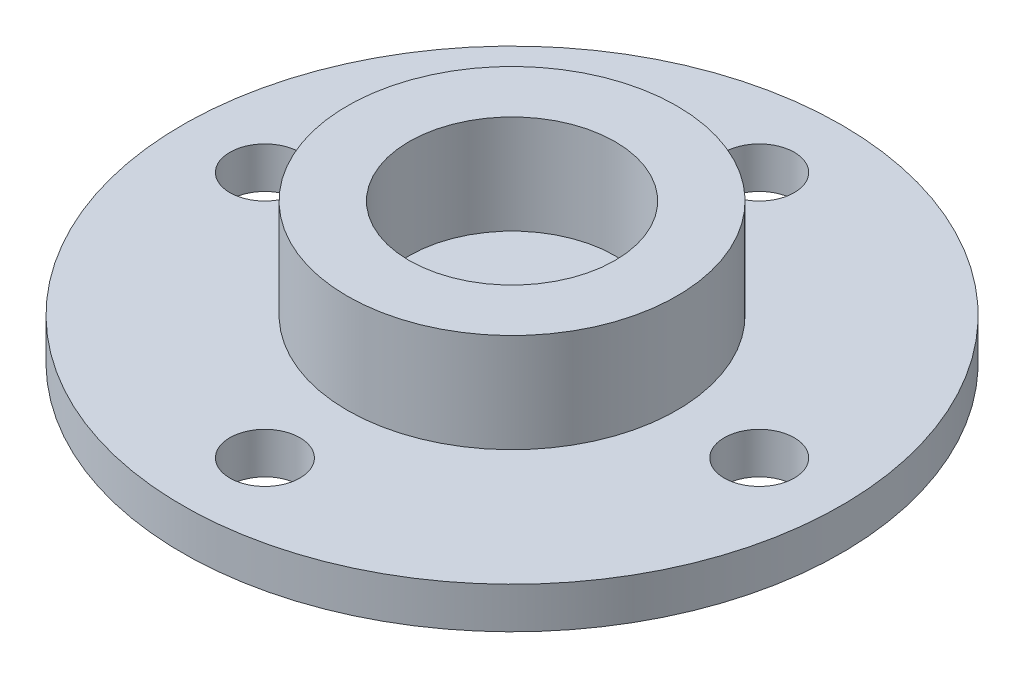
SolidWorks part; units mm, degrees
ref_plane "Front Plane" through (0, 0, 0) normal (0, 0, 1) x (1, 0, 0)
ref_plane "Top Plane" through (0, 0, 0) normal (0, 1, 0) x (1, 0, 0)
ref_plane "Right Plane" through (0, 0, 0) normal (1, 0, 0) x (0, 0, -1)
sketch "Sketch1" plane through (0, 0, 0) normal (0, 0, 1) x (1, 0, 0)
  line L0 (4.5, 5) -> (12.5, 5)
  line L1 (12.5, 5) -> (12.5, 17)
  line L2 (12.5, 17) -> (20, 17)
  line L3 (20, 17) -> (20, 5)
  line L4 (20, 5) -> (40, 5)
  line L5 (40, 5) -> (40, 0)
  line L6 (40, 0) -> (4.5, 0)
  line L7 (4.5, 0) -> (4.5, 5)
  line L8 (0, 0) -> (0, 22.5) construction
  dimension "D1" = 9
  dimension "D2" = 40
  dimension "D3" = 80
  dimension "D4" = 5
  dimension "D5" = 5
  dimension "D6" = 12
  dimension "D7" = 25
revolve "Revolve1" add sketch "Sketch1" angle 360 about L8
sketch "Sketch2" plane through (0, 0, 0) normal (0, -1, 0) x (1, 0, 0)
  circle A0 centre (0, 0) radius 30 construction
  circle A1 centre (0, 30) radius 4.25
  circle A2 centre (30, 0) radius 4.25
  circle A3 centre (0, -30) radius 4.25
  circle A4 centre (-30, 0) radius 4.25
  point P5 (28.8413, -8.2572)
  point P6 (0, 0)
  point P14 (0, 0)
  dimension "D1" = 60
  dimension "D2" = 8.5
  dimension "D3" = 4
extrude "Cut-Extrude1" cut sketch "Sketch2" against normal blind 10
